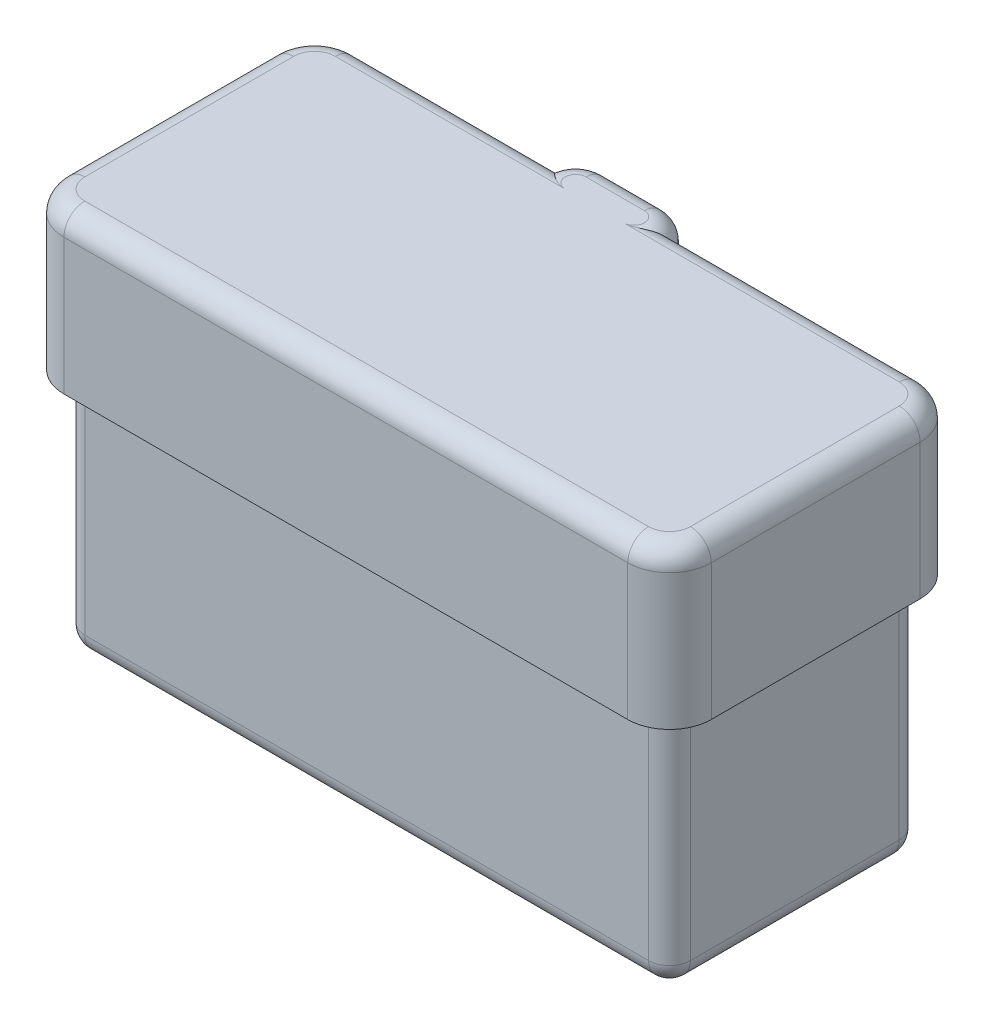
SolidWorks part; units mm, degrees
ref_plane "正面" through (0, 0, 0) normal (0, 0, 1) x (1, 0, 0)
ref_plane "平面" through (0, 0, 0) normal (0, 1, 0) x (1, 0, 0)
ref_plane "右側面" through (0, 0, 0) normal (1, 0, 0) x (0, 0, -1)
sketch "ｽｹｯﾁ1" plane through (0, 0, 0) normal (0, 1, 0) x (1, 0, 0)
  line L1 (-29, 12) -> (29, 12)
  line L2 (-29, 12) -> (-29, -12)
  line L3 (-29, -12) -> (29, -12)
  line L4 (29, 12) -> (29, -12)
  line L5 (-29, 12) -> (29, -12) construction
  line L6 (-29, -12) -> (29, 12) construction
  point P0 (0, 0)
  dimension "D1" = 24
  dimension "D2" = 58
extrude "ﾎﾞｽ - 押し出し1" add sketch "ｽｹｯﾁ1" along normal blind 23
sketch "ｽｹｯﾁ2" plane through (0, 23, 0) normal (0, 1, 0) x (1, 0, 0)
  line L0 (-6, 12) -> (-6, 13)
  line L1 (29, 12) -> (-29, 12) construction
  line L2 (-5, 14) -> (-3, 14)
  line L3 (-3, 14) -> (-3, 13)
  line L4 (-3, 13) -> (-5, 13)
  line L5 (-5, 13) -> (-5, 12)
  line L6 (-5, 12) -> (-6, 12)
  line L8 (-2.2, 15) -> (-2.2, 20.5344) construction
  line L9 (1.6, 12) -> (1.6, 13)
  line L10 (0.6, 13) -> (0.6, 12)
  line L11 (-1.4, 13) -> (0.6, 13)
  line L12 (-1.4, 14) -> (-1.4, 13)
  line L13 (0.6, 14) -> (-1.4, 14)
  arc A0 (-6, 13) -> (-5, 14) centre (-5, 13) cw
  arc A1 (1.6, 13) -> (0.6, 14) centre (0.6, 13) ccw
  point P4 (0, 12)
  point P11 (-6, 14)
  line M8 (29, 12) -> (-29, 12)
  dimension "D6" = 1
  dimension "D1" = 2
  dimension "D2" = 1
  dimension "D3" = 1
  dimension "D4" = 5
  dimension "D5" = 3
  dimension "D7" = 0.8
  dimension "D8" = 2
extrude "ﾎﾞｽ - 押し出し2" add sketch "ｽｹｯﾁ2" against normal blind 20 contours L9 A1 L13 L12 L11 L10 M8 | L2 L3 L4 L5 L6 L0 A0
sketch "ｽｹｯﾁ3" plane through (0, 23, 0) normal (0, 1, 0) x (1, 0, 0)
  line L1 (-26, -9) -> (26, -9)
  line L2 (-26, -9) -> (-26, 9)
  line L3 (-26, 9) -> (26, 9)
  line L4 (26, -9) -> (26, 9)
  line L5 (-26, -9) -> (26, 9) construction
  line L6 (-26, 9) -> (26, -9) construction
  point P0 (0, 0)
  dimension "D1" = 18
  dimension "D2" = 52
extrude "ｶｯﾄ - 押し出し1" cut sketch "ｽｹｯﾁ3" against normal blind 15
fillet "ﾌｨﾚｯﾄ1" radius 2 12 edges at (0, 0, -12) (-29, 0, 0) (0, 0, 12) (29, 0, 0) (-26, 15.5, 9) (-26, 15.5, -9) (26, 15.5, 9) (26, 15.5, -9) (-29, 11.5, 12) (-29, 11.5, -12) (29, 11.5, 12) (29, 11.5, -12)
sketch "ｽｹｯﾁ4" plane through (0, 23, 0) normal (0, 1, 0) x (1, 0, 0)
  line L1 (-27, -12) -> (27, -12) construction
  line L34 (-27, -12) -> (27, -12)
  line L35 (31, -10) -> (31, 10)
  line L36 (27, 14) -> (3.4284, 14)
  line L37 (3.4284, 14) -> (3.4284, 14)
  line L38 (0.6, 16) -> (-2.2, 16)
  line L39 (-2.2, 16) -> (-2.2, 16)
  line L40 (-2.2, 16) -> (-2.2, 16)
  line L41 (-2.2, 16) -> (-2.2, 16)
  line L42 (-2.2, 16) -> (-2.2, 16)
  line L43 (-2.2, 16) -> (-2.2, 16)
  line L44 (-2.2, 16) -> (-2.2, 16)
  line L45 (-2.2, 16) -> (-2.2, 16)
  line L46 (-2.2, 16) -> (-5, 16)
  line L47 (-7.8284, 14) -> (-7.8284, 14)
  line L48 (-7.8284, 14) -> (-27, 14)
  line L49 (-31, 10) -> (-31, -10)
  line L50 (-27, -14) -> (27, -14)
  line L51 (-29, 10) -> (-29, -10)
  line L52 (-27, -12) -> (27, -12)
  line L53 (29, -10) -> (29, 10)
  line L54 (27, 12) -> (1.6, 12)
  line L55 (1.6, 12) -> (1.6, 13)
  line L56 (0.6, 14) -> (-1.4, 14)
  line L57 (-1.4, 14) -> (-1.4, 13)
  line L58 (-1.4, 13) -> (0.6, 13)
  line L59 (0.6, 13) -> (0.6, 12)
  line L60 (0.6, 12) -> (-5, 12)
  line L61 (-5, 12) -> (-5, 13)
  line L62 (-5, 13) -> (-3, 13)
  line L63 (-3, 13) -> (-3, 14)
  line L64 (-3, 14) -> (-5, 14)
  line L65 (-6, 13) -> (-6, 12)
  line L66 (-6, 12) -> (-27, 12)
  line L67 (-29, 10) -> (-29, -10)
  line L68 (-27, -12) -> (27, -12)
  line L69 (29, -10) -> (29, 10)
  line L70 (27, 12) -> (1.6, 12)
  line L71 (1.6, 12) -> (1.6, 13)
  line L72 (0.6, 14) -> (-1.4, 14)
  line L73 (-1.4, 14) -> (-3, 14)
  line L76 (0.6, 12) -> (-5, 12)
  line L80 (-3, 14) -> (-5, 14)
  line L81 (-6, 13) -> (-6, 12)
  line L82 (-6, 12) -> (-27, 12)
  line L83 (0.6, 13) -> (0.6, 12) construction
  line L84 (-1.4, 13) -> (0.6, 13) construction
  line L85 (-5, 12) -> (-5, 13) construction
  line L86 (-5, 13) -> (-3, 13) construction
  line L87 (-3, 13) -> (-3, 14) construction
  line L88 (-1.4, 14) -> (-1.4, 13) construction
  arc A12 (27, -14) -> (31, -10) centre (27, -10) ccw
  arc A13 (31, 10) -> (27, 14) centre (27, 10) ccw
  arc A14 (3.4284, 14) -> (0.6, 16) centre (0.6, 13) ccw
  arc A15 (-5, 16) -> (-7.8284, 14) centre (-5, 13) ccw
  arc A16 (-27, 14) -> (-31, 10) centre (-27, 10) ccw
  arc A17 (-31, -10) -> (-27, -14) centre (-27, -10) ccw
  arc A18 (-29, -10) -> (-27, -12) centre (-27, -10) ccw
  arc A19 (27, -12) -> (29, -10) centre (27, -10) ccw
  arc A20 (29, 10) -> (27, 12) centre (27, 10) ccw
  arc A21 (1.6, 13) -> (0.6, 14) centre (0.6, 13) ccw
  arc A22 (-5, 14) -> (-6, 13) centre (-5, 13) ccw
  arc A23 (-27, 12) -> (-29, 10) centre (-27, 10) ccw
  arc A24 (-29, -10) -> (-27, -12) centre (-27, -10) ccw
  arc A25 (27, -12) -> (29, -10) centre (27, -10) ccw
  arc A26 (29, 10) -> (27, 12) centre (27, 10) ccw
  arc A27 (1.6, 13) -> (0.6, 14) centre (0.6, 13) ccw
  arc A28 (-5, 14) -> (-6, 13) centre (-5, 13) ccw
  arc A29 (-27, 12) -> (-29, 10) centre (-27, 10) ccw
  line M32 (-29, 10) -> (-29, -10)
  arc M33 (-29, -10) -> (-27, -12) centre (-27, -10) ccw
  line M34 (-27, -12) -> (27, -12)
  arc M35 (27, -12) -> (29, -10) centre (27, -10) ccw
  line M36 (29, -10) -> (29, 10)
  arc M37 (29, 10) -> (27, 12) centre (27, 10) ccw
  line M38 (27, 12) -> (1.6, 12)
  line M39 (1.6, 12) -> (1.6, 13)
  arc M40 (1.6, 13) -> (0.6, 14) centre (0.6, 13) ccw
  line M41 (0.6, 14) -> (-1.4, 14)
  line M49 (-3, 14) -> (-5, 14)
  arc M50 (-5, 14) -> (-6, 13) centre (-5, 13) ccw
  line M51 (-6, 13) -> (-6, 12)
  line M52 (-6, 12) -> (-27, 12)
  arc M53 (-27, 12) -> (-29, 10) centre (-27, 10) ccw
  dimension "D1" = 0
  dimension "D2" = 2
extrude "ﾎﾞｽ - 押し出し3" add sketch "ｽｹｯﾁ4" along normal blind 15 separate body contours L49 A17 L50 A12 L35 A13 L36 A14 L38 L46 A15 L48 A16 L73 M41 M40 M39 M38 M37 M36 M35 M34 M33 M32 M53 M52 M51 M50 M49
sketch "ｽｹｯﾁ5" plane through (0, 0, 0) normal (0, 0, 1) x (1, 0, 0)
  line L3 (-31, 38) -> (-31, 23) construction
  line L4 (-29, 2) -> (-29, 23) construction
  line L5 (-31, 23) -> (-27, 23) construction
  line L6 (-31, 25.9418) -> (-31, 18.1167) construction
  line L7 (-31, 24.8163) -> (-31, 24)
  line L8 (-29, 21.1056) -> (-29, 20.3)
  arc A0 (-31, 24) -> (-29.1905, 21.1482) centre (-31, 22) ccw
  arc A1 (-31, 24.8163) -> (-29, 20.3) centre (-31, 22.1153) ccw
  arc A2 (-29.1905, 21.1482) -> (-29, 21.1056) centre (-29.1, 21.1056) cw
  point P18 (-29, 22)
  dimension "D1" = 2
  dimension "D3" = 2.701
  dimension "D5" = 0.1
  dimension "D2" = 1
  dimension "D4" = 1.7
extrude "ﾎﾞｽ - 押し出し9" add sketch "ｽｹｯﾁ5" along normal blind 2.5 and the other way blind 2.5
sketch "ｽｹｯﾁ6" plane through (0, 38, 0) normal (0, 1, 0) x (1, 0, 0)
  line L0 (0.6, 16) -> (-5, 16) construction
  line L1 (-7.8284, 14) -> (-27, 14) construction
  line L2 (-31, 10) -> (-31, -10) construction
  line L3 (-27, -14) -> (27, -14) construction
  line L4 (31, -10) -> (31, 10) construction
  line L5 (27, 14) -> (3.4284, 14) construction
  line L6 (0.6, 16) -> (-5, 16)
  line L7 (-7.8284, 14) -> (-27, 14)
  line L8 (-31, 10) -> (-31, -10)
  line L9 (-27, -14) -> (27, -14)
  line L10 (31, -10) -> (31, 10)
  line L11 (27, 14) -> (3.4284, 14)
  arc A0 (-5, 16) -> (-7.8284, 14) centre (-5, 13) ccw construction
  arc A1 (-27, 14) -> (-31, 10) centre (-27, 10) ccw construction
  arc A2 (-31, -10) -> (-27, -14) centre (-27, -10) ccw construction
  arc A3 (27, -14) -> (31, -10) centre (27, -10) ccw construction
  arc A4 (31, 10) -> (27, 14) centre (27, 10) ccw construction
  arc A5 (3.4284, 14) -> (0.6, 16) centre (0.6, 13) ccw construction
  arc A6 (-5, 16) -> (-7.8284, 14) centre (-5, 13) ccw
  arc A7 (-27, 14) -> (-31, 10) centre (-27, 10) ccw
  arc A8 (-31, -10) -> (-27, -14) centre (-27, -10) ccw
  arc A9 (27, -14) -> (31, -10) centre (27, -10) ccw
  arc A10 (31, 10) -> (27, 14) centre (27, 10) ccw
  arc A11 (3.4284, 14) -> (0.6, 16) centre (0.6, 13) ccw
extrude "ﾎﾞｽ - 押し出し10" add sketch "ｽｹｯﾁ6" against normal blind 5
fillet "ﾌｨﾚｯﾄ3" radius 2 9 edges at (-17.4142, 38, -14) (-29.8284, 38, -12.8284) (-31, 38, 0) (-29.8284, 38, 12.8284) (0, 38, 14) (29.8284, 38, 12.8284) (15.2142, 38, -14) (29.8284, 38, -12.8284) (31, 38, 0)
fillet "ﾌｨﾚｯﾄ4" radius 2 3 edges at (-7.4495, 38, -14.7321) (-2.2, 38, -16) (3.0495, 38, -14.7321)
sketch "ｽｹｯﾁ7" plane through (0, 0, 0) normal (0, -1, 0) x (1, 0, 0)
  circle A0 centre (-15, 5) radius 1.5
  circle A1 centre (0, 5) radius 1.5
  circle A2 centre (15, 5) radius 1.5
  circle A3 centre (0, -5) radius 1
  circle A4 centre (7, -5) radius 1
  circle A5 centre (14, -5) radius 1
  circle A6 centre (-7, -5) radius 1
  circle A7 centre (-14, -5) radius 1
  dimension "D1" = 3
  dimension "D6" = 2
  dimension "D2" = 15
  dimension "D3" = 5
  dimension "D4" = 15
  dimension "D5" = 5
  dimension "D7" = 7
  dimension "D8" = 7
  dimension "D9" = 7
  dimension "D10" = 7
extrude "ｶｯﾄ - 押し出し2" cut sketch "ｽｹｯﾁ7" against normal blind 0.1
